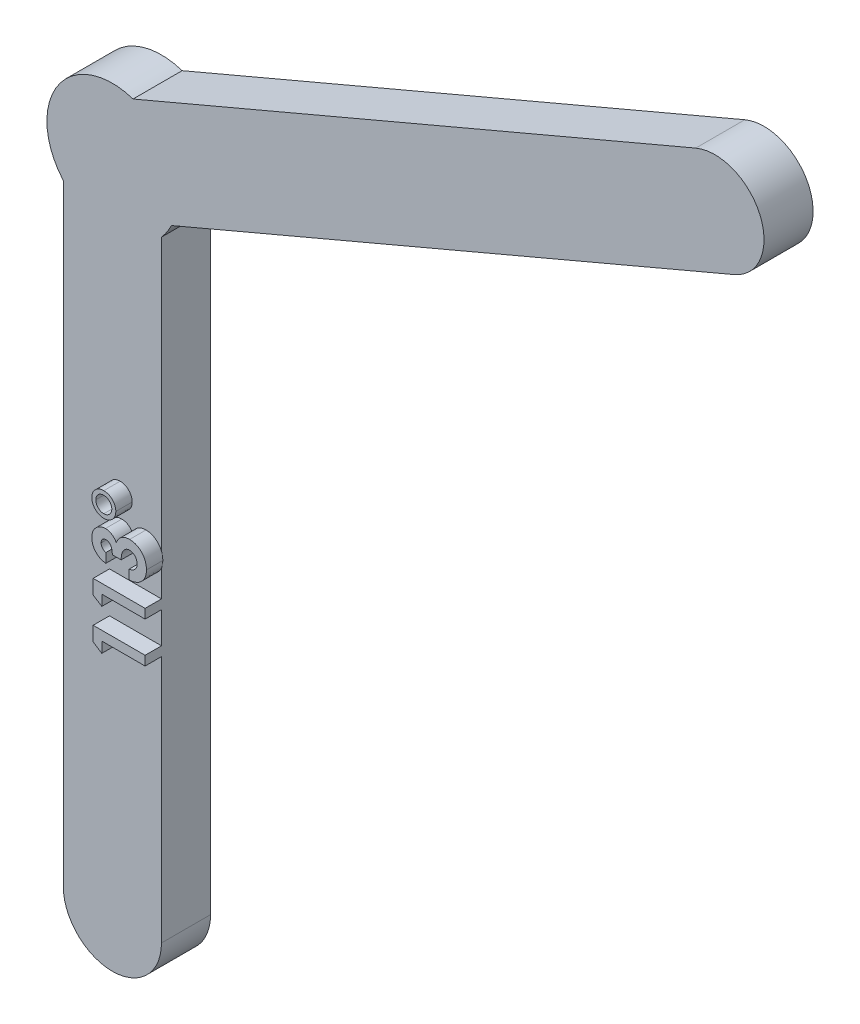
SolidWorks part; units mm, degrees
ref_plane "Front Plane" through (0, 0, 0) normal (0, 0, 1) x (1, 0, 0)
ref_plane "Top Plane" through (0, 0, 0) normal (0, 1, 0) x (1, 0, 0)
ref_plane "Right Plane" through (0, 0, 0) normal (1, 0, 0) x (0, 0, -1)
sketch "Sketch2" plane through (0, 0, 0) normal (0, 0, 1) x (1, 0, 0)
  line L0 (0, 0) -> (0, -40) construction
  line L1 (0, 0) -> (36.8202, 15.6292) construction
  line L2 (35.648, 18.3908) -> (37.9924, 12.8677) construction
  line L3 (-3, -40) -> (3, -40) construction
  line L4 (-3, -40) -> (-3, -2.6458)
  line L5 (3, -40) -> (3, -2.6458)
  line L6 (35.648, 18.3908) -> (1.2632, 3.7953)
  line L7 (37.9924, 12.8677) -> (3.6076, -1.7277)
  arc A0 (1.2632, 3.7953) -> (-3, -2.6458) centre (0, 0) ccw
  arc A1 (-3, -40) -> (3, -40) centre (0, -40) ccw
  arc A2 (35.648, 18.3908) -> (37.9924, 12.8677) centre (36.8202, 15.6292) cw
  arc A3 (3, -2.6458) -> (3.6076, -1.7277) centre (0, 0) ccw
  point P12 (36.8202, 15.6292)
  dimension "D3" = 3
  dimension "D4" = 8
  dimension "D1" = 40
  dimension "D2" = 113
extrude "Boss-Extrude1" add sketch "Sketch2" along normal blind 3
sketch "Sketch3" plane through (0, 0, 3) normal (0, 0, 1) x (1, 0, 0)
  text T0 "<b>113°</b>"
extrude "Boss-Extrude2" add sketch "Sketch3" along normal blind 1
